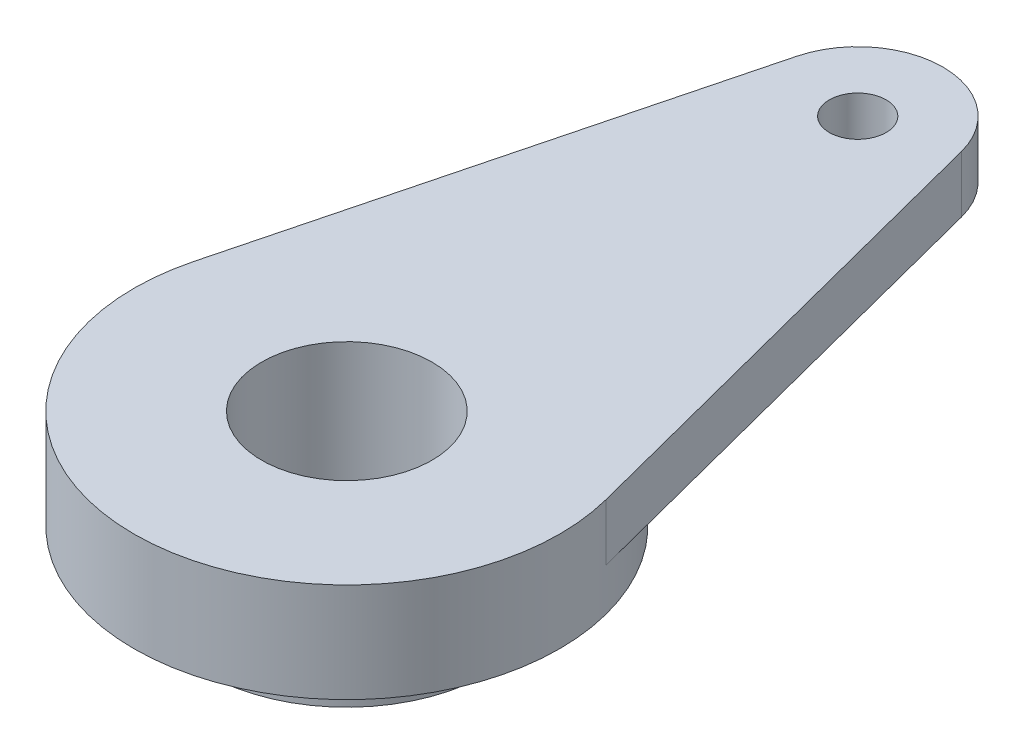
SolidWorks part; units mm, degrees
ref_plane "前视基准面" through (0, 0, 0) normal (0, 0, 1) x (1, 0, 0)
ref_plane "上视基准面" through (0, 0, 0) normal (0, 1, 0) x (1, 0, 0)
ref_plane "右视基准面" through (0, 0, 0) normal (1, 0, 0) x (0, 0, -1)
sketch "草图1" plane through (0, 0, 0) normal (0, 1, 0) x (1, 0, 0)
  circle A0 centre (0, 0) radius 5
  dimension "D1" = 10
extrude "凸台-拉伸1" add sketch "草图1" along normal blind 2
sketch "草图2" plane through (0, 2, 0) normal (0, 1, 0) x (1, 0, 0)
  circle A0 centre (0, 0) radius 7.5
  dimension "D1" = 15
extrude "凸台-拉伸2" add sketch "草图2" along normal blind 1.5
sketch "草图3" plane through (0, 3.5, 0) normal (0, 1, 0) x (1, 0, 0)
  line L0 (0, 18) -> (0, 0) construction
  line L1 (-2.9047, 18.75) -> (-7.2618, 1.875)
  line L2 (2.9047, 18.75) -> (7.2618, 1.875)
  arc A0 (-7.2618, 1.875) -> (7.2618, 1.875) centre (0, 0) ccw
  arc A1 (2.9047, 18.75) -> (-2.9047, 18.75) centre (0, 18) ccw
  circle A2 centre (0, 18) radius 1
  dimension "D2" = 2
  dimension "D3" = 6
  dimension "D4" = 15
  dimension "D1" = 18
extrude "凸台-拉伸3" add sketch "草图3" along normal blind 2
sketch "草图4" plane through (0, 0, 0) normal (0, -1, 0) x (1, 0, 0)
  circle A0 centre (0, 0) radius 3
  dimension "D1" = 6
extrude "切除-拉伸1" cut sketch "草图4" against normal through all
